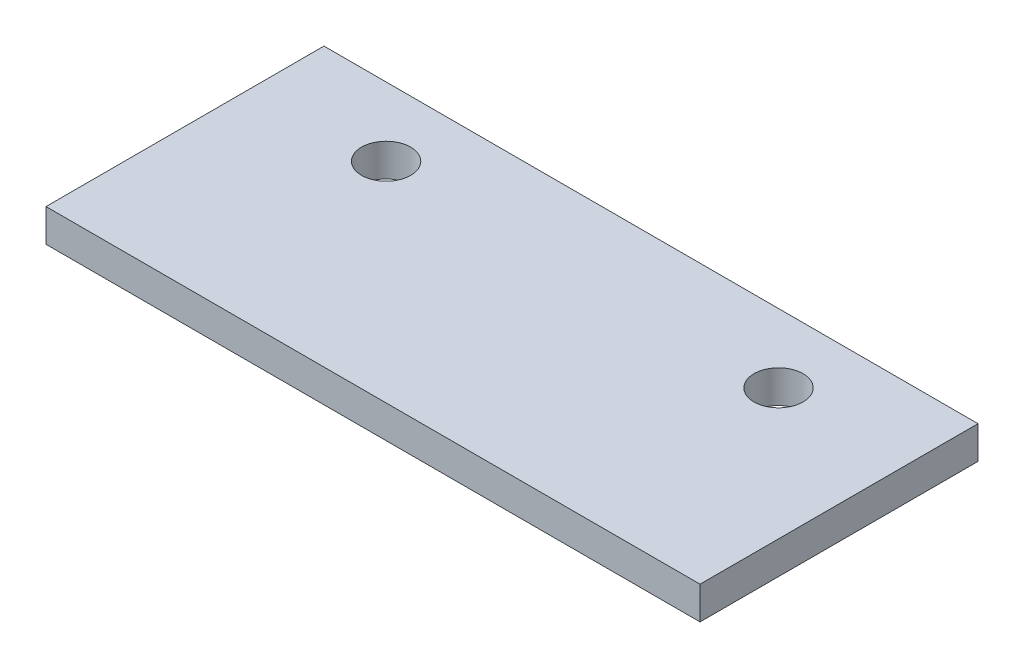
SolidWorks part; units mm, degrees
material "Plain Carbon Steel"
ref_plane "Front Plane" through (0, 0, 0) normal (0, 0, 1) x (1, 0, 0)
ref_plane "Top Plane" through (0, 0, 0) normal (0, 1, 0) x (1, 0, 0)
ref_plane "Right Plane" through (0, 0, 0) normal (1, 0, 0) x (0, 0, -1)
sketch "Sketch1" plane through (0, 0, 0) normal (0, 1, 0) x (1, 0, 0)
  line L1 (100, -42.5) -> (-100, -42.5)
  line L2 (100, -42.5) -> (100, 42.5)
  line L3 (100, 42.5) -> (-100, 42.5)
  line L4 (-100, -42.5) -> (-100, 42.5)
  line L5 (100, -42.5) -> (-100, 42.5) construction
  line L6 (100, 42.5) -> (-100, -42.5) construction
  point P0 (0, 0)
  dimension "D1" = 85
  dimension "D2" = 200
extrude "Boss-Extrude1" add sketch "Sketch1" along normal blind 10
sketch "Sketch2" plane through (0, 10, 0) normal (0, 1, 0) x (1, 0, 0)
  line L0 (100, 42.5) -> (-100, 42.5) construction
  line L1 (-100, 42.5) -> (-100, -42.5) construction
  circle A0 centre (-60, 21.5) radius 7.5
  dimension "D1" = 21
  dimension "D2" = 40
  dimension "D3" = 15
extrude "Cut-Extrude1" cut sketch "Sketch2" against normal blind 10
mirror "Mirror1" about plane through (0, 0, 0) normal (1, 0, 0) of "Cut-Extrude1"
